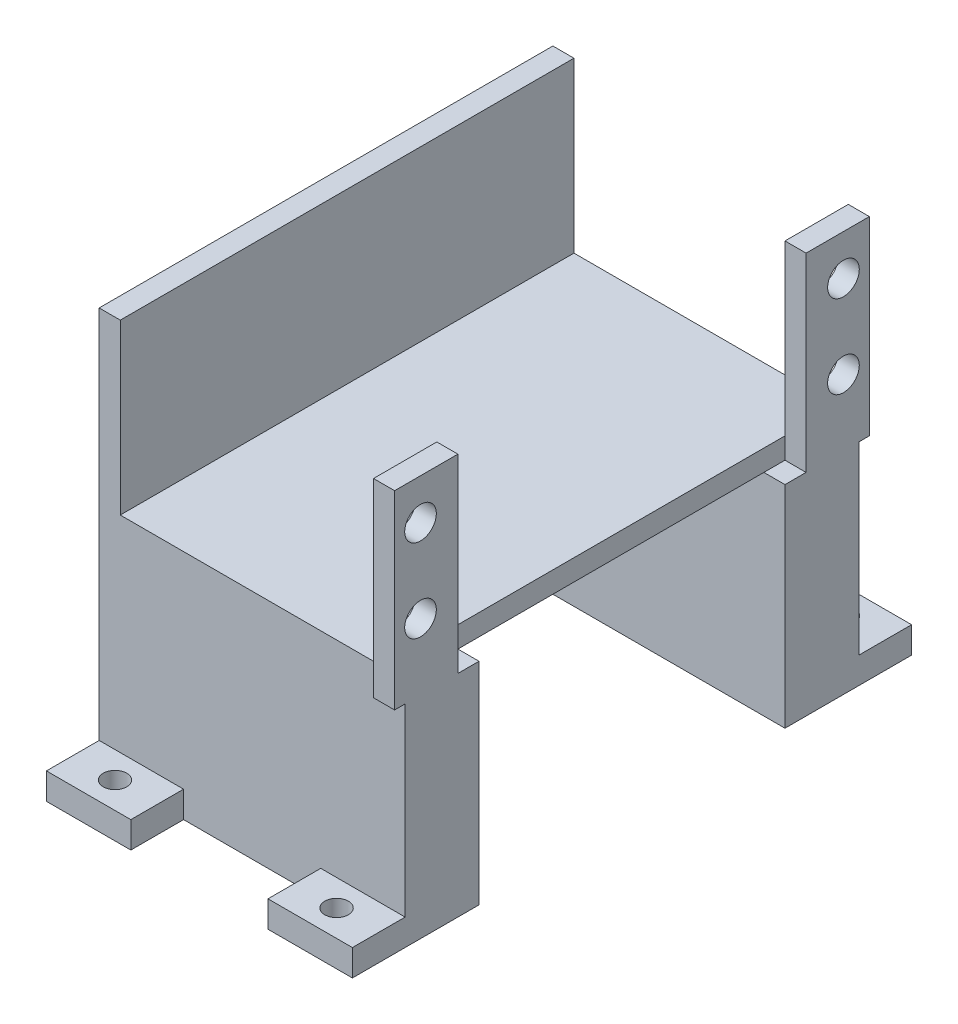
SolidWorks part; units mm, degrees
material "ABS"
ref_plane "Front" through (0, 0, 0) normal (0, 0, 1) x (1, 0, 0)
ref_plane "Top" through (0, 0, 0) normal (0, 1, 0) x (1, 0, 0)
ref_plane "Right" through (0, 0, 0) normal (1, 0, 0) x (0, 0, -1)
sketch "Sketch1" plane through (0, 0, 0) normal (0, 1, 0) x (1, 0, 0)
  line L1 (0, 0) -> (31.75, 0)
  line L2 (0, 0) -> (0, 54.61)
  line L3 (0, 54.61) -> (31.75, 54.61)
  line L4 (31.75, 0) -> (31.75, 54.61)
  dimension "D1" = 31.75
  dimension "D2" = 54.61
extrude "Boss-Extrude1" add sketch "Sketch1" along normal blind 2.54 contours L1 L4 L3 L2
sketch "Sketch2" plane through (0, 0, 0) normal (0, 1, 0) x (1, 0, 0)
  line L0 (31.75, 27.305) -> (-11.8437, 27.305) construction
  line L1 (31.75, -1.27) -> (34.29, -1.27)
  line L2 (31.75, -1.27) -> (31.75, 6.35)
  line L3 (31.75, 6.35) -> (34.29, 6.35)
  line L4 (34.29, -1.27) -> (34.29, 6.35)
  line L6 (31.75, 0) -> (31.75, 54.61) construction
  line L7 (31.75, 48.26) -> (34.29, 48.26)
  line L8 (34.29, 55.88) -> (34.29, 48.26)
  line L9 (31.75, 55.88) -> (34.29, 55.88)
  line L10 (31.75, 55.88) -> (31.75, 48.26)
  line L11 (0, 0) -> (31.75, 0) construction
  line L12 (0, 0) -> (-2.54, 0)
  line L13 (0, 0) -> (0, 54.61)
  line L14 (0, 54.61) -> (-2.54, 54.61)
  line L15 (-2.54, 0) -> (-2.54, 54.61)
  point P8 (31.75, 27.305)
  dimension "D1" = 7.62
  dimension "D2" = 2.54
  dimension "D3" = 2.54
  dimension "D4" = 1.27
extrude "Boss-Extrude2" add sketch "Sketch2" along normal blind 22.86
sketch "Sketch3" plane through (0, 0, 0) normal (0, -1, 0) x (1, 0, 0)
  line L0 (34.29, 1.27) -> (34.29, -6.35) construction
  line L1 (-2.54, 0) -> (34.29, 0)
  line L2 (-2.54, 0) -> (-2.54, -8.89)
  line L3 (-2.54, -8.89) -> (34.29, -8.89)
  line L4 (34.29, 0) -> (34.29, -8.89)
  line L5 (-2.54, -27.305) -> (39.9335, -27.305) construction
  line L8 (31.75, -6.35) -> (31.75, -48.26) construction
  line L9 (-2.54, -45.72) -> (34.29, -45.72)
  line L10 (34.29, -54.61) -> (34.29, -45.72)
  line L11 (-2.54, -54.61) -> (34.29, -54.61)
  line L12 (-2.54, -54.61) -> (-2.54, -45.72)
  point P10 (31.75, -27.305)
  dimension "D1" = 8.89
extrude "Boss-Extrude3" add sketch "Sketch3" along normal blind 25.4
sketch "Sketch4" plane through (34.29, 0, 0) normal (1, 0, 0) x (0, 0, -1)
  line L1 (27.305, -7.6729) -> (27.305, 45.0882) construction
  line L2 (6.35, 2.54) -> (48.26, 2.54) construction
  circle A0 centre (1.85, 17.9678) radius 1.905
  circle A1 centre (1.85, 7.9678) radius 1.905
  circle A2 centre (52.76, 17.9678) radius 1.905
  circle A3 centre (52.76, 7.9678) radius 1.905
  arc A4 (-0.1731, 16.2178) -> (-0.1731, 19.7178) centre (1.85, 17.9678) ccw construction
  arc A5 (0.205, 6.5449) -> (0.205, 9.3907) centre (1.85, 7.9678) ccw construction
  point P11 (27.305, 2.54)
  dimension "D1" = 3.81
  dimension "D2" = 3.81
extrude "Cut-Extrude1" cut sketch "Sketch4" against normal up to surface (2.54 mm away) up to face at (31.75, 8.4667, -52.9167)
sketch "Sketch5" plane through (0, 0, -54.61) normal (0, 0, -1) x (-1, 0, 0)
  line L1 (-34.29, -25.4) -> (-24.13, -25.4)
  line L2 (-34.29, -25.4) -> (-34.29, -22.225)
  line L3 (-34.29, -22.225) -> (-24.13, -22.225)
  line L4 (-24.13, -25.4) -> (-24.13, -22.225)
  line L5 (2.54, -25.4) -> (-7.62, -25.4)
  line L6 (2.54, -25.4) -> (2.54, -22.225)
  line L7 (2.54, -22.225) -> (-7.62, -22.225)
  line L8 (-7.62, -25.4) -> (-7.62, -22.225)
  dimension "D1" = 10.16
  dimension "D2" = 3.175
  dimension "D3" = 3.175
  dimension "D4" = 10.16
extrude "Boss-Extrude4" add sketch "Sketch5" along normal blind 6.35
sketch "Sketch6" plane through (0, 0, 0) normal (0, 0, 1) x (1, 0, 0)
  line L1 (34.29, -25.4) -> (24.13, -25.4)
  line L2 (34.29, -25.4) -> (34.29, -22.225)
  line L3 (34.29, -22.225) -> (24.13, -22.225)
  line L4 (24.13, -25.4) -> (24.13, -22.225)
  line L5 (-2.54, -25.4) -> (7.62, -25.4)
  line L6 (-2.54, -25.4) -> (-2.54, -22.225)
  line L7 (-2.54, -22.225) -> (7.62, -22.225)
  line L8 (7.62, -25.4) -> (7.62, -22.225)
  dimension "D1" = 10.16
  dimension "D2" = 10.16
  dimension "D3" = 3.175
  dimension "D4" = 3.175
extrude "Boss-Extrude5" add sketch "Sketch6" along normal blind 6.35
sketch "Sketch7" plane through (0, -22.225, 0) normal (0, 1, 0) x (1, 0, 0)
  line L0 (24.13, 60.96) -> (34.29, 60.96) construction
  line L1 (34.29, 60.96) -> (34.29, 54.61) construction
  line L2 (34.29, -6.35) -> (24.13, -6.35) construction
  line L3 (7.62, -6.35) -> (-2.54, -6.35) construction
  line L4 (-2.54, -6.35) -> (-2.54, 0) construction
  line L5 (24.13, -6.35) -> (24.13, 0) construction
  line L6 (-2.54, 60.96) -> (-2.54, 54.61) construction
  line L7 (-2.54, 60.96) -> (7.62, 60.96) construction
  circle A0 centre (29.21, 57.785) radius 1.4224
  circle A1 centre (2.54, 57.785) radius 1.4224
  circle A2 centre (2.54, -3.175) radius 1.4224
  circle A3 centre (29.21, -3.175) radius 1.4224
  point P20 (24.13, -3.175)
  dimension "D1" = 2.8448
  dimension "D2" = 3.175
  dimension "D3" = 5.08
  dimension "D4" = 3.175
  dimension "D5" = 3.175
  dimension "D6" = 5.08
  dimension "D7" = 5.08
  dimension "D8" = 5.08
  dimension "D9" = 3.175
extrude "Cut-Extrude2" cut sketch "Sketch7" against normal through all
